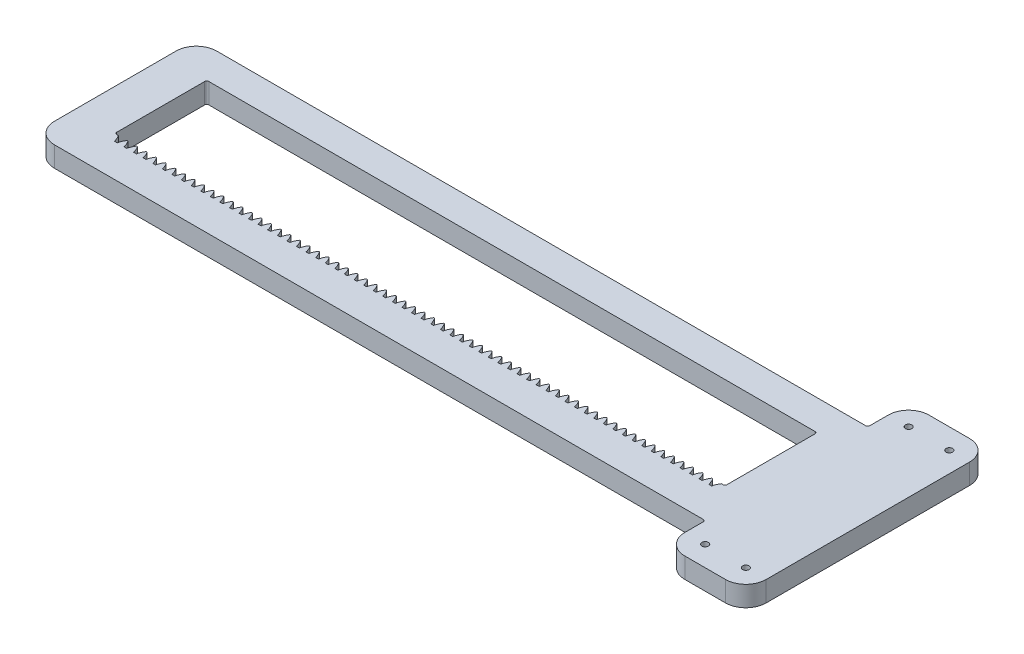
SolidWorks part; units mm, degrees
material "Acrylic (Medium-high impact)"
ref_plane "Front Plane" through (0, 0, 0) normal (0, 0, 1) x (1, 0, 0)
ref_plane "Top Plane" through (0, 0, 0) normal (0, 1, 0) x (1, 0, 0)
ref_plane "Right Plane" through (0, 0, 0) normal (1, 0, 0) x (0, 0, -1)
sketch "Sketch1" plane through (0, 0, 0) normal (0, 1, 0) x (1, 0, 0)
  line L8 (-150, -20.25) -> (150, -20.25)
  line L13 (150, -20.25) -> (150, 25)
  line L14 (150, 25) -> (-150, 25)
  line L15 (-150, 25) -> (-150, -20.25)
  line L16 (0, 25) -> (0, -20.25) construction
  line L17 (-170, 0) -> (200, 0) construction
  line L18 (-170, 39.9) -> (-170, -39.9)
  line L19 (-170, -39.9) -> (160, -39.9)
  line L20 (200, -39.9) -> (200, 39.9)
  line L21 (160, 39.9) -> (-170, 39.9)
  line L22 (200, 39.9) -> (200, 60)
  line L23 (200, 60) -> (160, 60)
  line L24 (160, 60) -> (160, 39.9)
  line L25 (200, -39.9) -> (200, -60)
  line L26 (200, -60) -> (160, -60)
  line L27 (160, -60) -> (160, -39.9)
  line L28 (160, -39.9) -> (160, 0) construction
  line L29 (200, 39.9) -> (160, 39.9) construction
  line L30 (160, 0) -> (160, 39.9) construction
  line L31 (160, -39.9) -> (200, -39.9) construction
  point P6 (0, -43.5)
  dimension "D1" = 43.5
  dimension "D2" = 23.25
  dimension "D3" = 79.8
  dimension "D4" = 25
  dimension "D5" = 20
  dimension "D6" = 50
  dimension "D7" = 300
  dimension "D8" = 120
  dimension "D10" = 40
extrude "Boss-Extrude1" add sketch "Sketch1" along normal mid plane 10
sketch "Sketch3" plane through (0, 0, 0) normal (0, 1, 0) x (1, 0, 0)
  line L0 (0, -43.5) -> (0, -16.6494) construction
  line L1 (0, -43.5) -> (-1.2702, -21.7871) construction
  line L2 (0, -43.5) -> (-4.6973, -0.3088) construction
  line L3 (-1.2702, -21.7871) -> (-2.3487, -21.9044) construction
  line L4 (-150, -20.25) -> (150, -20.25) construction
  arc A0 (0.6969, -23.6382) -> (-0.6969, -23.6382) centre (0, -43.5) ccw
  arc A1 (2.1373, -20.25) -> (-2.1373, -20.25) centre (0, -43.5) ccw
  circle A2 centre (0, -43.5) radius 21.75 construction
  circle A3 centre (0, -43.5) radius 20.4383 construction
  arc A4 (-0.6969, -23.6382) -> (-2.1373, -20.25) centre (-9.2423, -25.2708) ccw
  arc A5 (2.1373, -20.25) -> (0.6969, -23.6382) centre (9.2423, -25.2708) ccw
  dimension "D1" = 39.748
  dimension "D3" = 43.5
  dimension "D6" = 40.8766
  dimension "D7" = 8.7
  dimension "D4" = 6.207
  dimension "D5" = 1.0848
extrude "Cut-Extrude1" cut sketch "Sketch3" against normal through all both and the other way through all
pattern_linear "LPattern1" count 32 spacing 4.7124 along (1, 0, 0) count 32 spacing 4.7124 along (-1, 0, 0) of "Cut-Extrude1"
sketch "Sketch4" plane through (0, 0, 0) normal (0, 1, 0) x (1, 0, 0)
  line L0 (-150, -21.75) -> (150, -21.75) construction
  line L1 (-150, 25) -> (-150, -20.25) construction
  line L2 (150, -20.25) -> (150, 25) construction
  dimension "D1" = 21.75
fillet "Fillet2" radius 1 4 edges at (150, 0, 20.25) (150, 0, -25) (-150, 0, 20.25) (-150, 0, -25)
sketch "Sketch5" plane through (0, 5, 0) normal (0, 1, 0) x (1, 0, 0)
  line L0 (200, -60) -> (200, 60) construction
  line L1 (170, 50) -> (190, 50) construction
  line L2 (170, 50) -> (170, -50) construction
  line L3 (170, -50) -> (190, -50) construction
  line L4 (190, 50) -> (190, -50) construction
  line L6 (190, 0) -> (200, 0) construction
  line L8 (200, -60) -> (200, 60) construction
  circle A0 centre (170, 50) radius 1.6
  circle A1 centre (190, 50) radius 1.6
  circle A2 centre (190, -50) radius 1.6
  circle A3 centre (170, -50) radius 1.6
  dimension "D1" = 10
  dimension "D5" = 3.2
  dimension "D2" = 100
  dimension "D4" = 20
extrude "Cut-Extrude2" cut sketch "Sketch5" against normal through all both and the other way through all
fillet "Fillet3" radius 10 4 edges at (160, 0, -60) (200, 0, -60) (160, 0, 60) (200, 0, 60)
fillet "Fillet4" radius 10 2 edges at (-170, 0, -39.9) (-170, 0, 39.9)
fillet "Fillet5" radius 1 2 edges at (160, 0, -39.9) (160, 0, 39.9)
